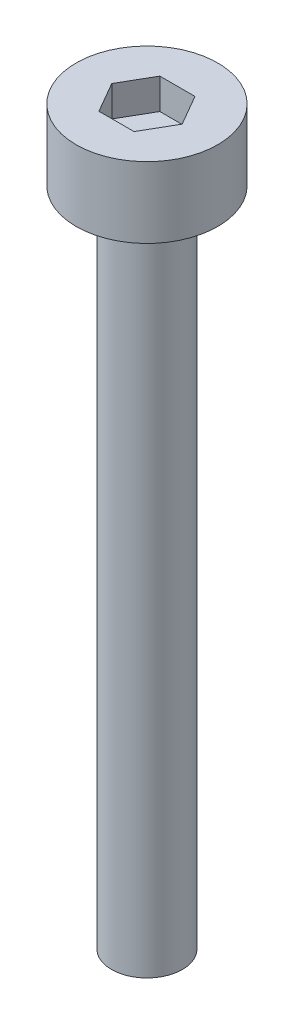
SolidWorks part; units mm, degrees
ref_plane "Front Plane" through (0, 0, 0) normal (0, 0, 1) x (1, 0, 0)
ref_plane "Top Plane" through (0, 0, 0) normal (0, 1, 0) x (1, 0, 0)
ref_plane "Right Plane" through (0, 0, 0) normal (1, 0, 0) x (0, 0, -1)
sketch "Sketch1" plane through (0, 0, 0) normal (0, 1, 0) x (1, 0, 0)
  circle A0 centre (0, 0) radius 1.5
  dimension "D1" = 3
extrude "ScrewShaft" add sketch "Sketch1" along normal blind 28
sketch "Sketch2" plane through (0, 28, 0) normal (0, 1, 0) x (1, 0, 0)
  circle A0 centre (0, 0) radius 3
  dimension "D1" = 6
extrude "Boss-Extrude2" add sketch "Sketch2" along normal blind 3
sketch "Sketch3" plane through (0, 31, 0) normal (0, 1, 0) x (1, 0, 0)
  line L0 (0, 0) -> (0, 1.29) construction
  line L1 (1.4896, 0) -> (0.7448, 1.29)
  line L2 (0.7448, 1.29) -> (-0.7448, 1.29)
  line L3 (-0.7448, 1.29) -> (-1.4896, 0)
  line L4 (-1.4896, 0) -> (-0.7448, -1.29)
  line L5 (-0.7448, -1.29) -> (0.7448, -1.29)
  line L6 (0.7448, -1.29) -> (1.4896, 0)
  circle A0 centre (0, 0) radius 1.29 construction
  dimension "D1" = 2.58
extrude "Cut-Extrude1" cut sketch "Sketch3" against normal blind 1.3
equation "\"X-ROD-SPACING\"=45"
equation "\"Y-ROD-SPACING\"=75"
equation "\"Z-ROD-SPACING\"=17.5"
equation "\"Y-BED-OFFSET\"=2"
equation "\"Y-BED-ROD-INSET\"=3.5"
equation "\"T-SLOT-NUT-FILLET-RADIUS\"=0.5"
equation "\"T-SLOT-SCREW-SHAFT-RADIUS\"=1.55"
equation "\"T-SLOT-SCREW-SHAFT-CUTOUT-LENGTH\"=11"
equation "\"T-SLOT-NUT-DEPTH\"=3.5"
equation "\"T-SLOT-NUT-WIDTH\"=2.85"
equation "\"T-SLOT-NUT-END-DISTANCE\"=8"
equation "\"ACRYLIC-THICKNESS\"=10"
equation "\"ACRYLIC-THICKNESS2\"=4.5"
equation "\"ACRYLIC-TAB-CUTOUT-SIZE\"=\"ACRYLIC-THICKNESS\"+\"ACRYLIC-TAB-TOLERANCE\"*2"
equation "\"ACRYLIC-TAB-WIDTH\"=\"ACRYLIC-THICKNESS\""
equation "\"ACRYLIC-M3-HOLE\"=2.9"
equation "\"SMOOTHROD-CAP-SCREW-DISTANCE\"=20"
equation "\"FRAME-WIDTH-INNER\"=370"
equation "\"NEMA17-HOLE-SPACING\"=31"
equation "\"NEMA17-CENTRAL-CUTOUT\"=22.5"
equation "\"Z-BRACKET-REACH\"=57"
equation "\"TOP-BRACKET-SPACING\"=40"
equation "\"SMOOTHROD-X-LENGTH\"=350"
equation "\"SMOOTHROD-Y-LENGTH\"=350"
equation "\"SMOOTHROD-Z-LENGTH\"=350"
equation "\"SMOOTHROD-TIGHTENING-HEADROOM\"=.25"
equation "\"LEADSCREW-Z-LENGTH\"=300"
equation "\"SCREW-LENGTH-FRAME\"=\"ACRYLIC-THICKNESS\" + 10"
equation "\"SCREW-HEAD-RADIUS\"=6"
equation "\"PRINTED-X-SMOOTHROD-DIAMETER\"=8.8"
equation "\"PRINTED-X-SMOOTHROD-CUTOUT\"=10"
equation "\"PRINTED-X-BASE-HEIGHT\"=10"
equation "\"PRINTED-LM8UU-CUTOUT-SIZE\"=15.5"
equation "\"PRINTED-LM8UU-CUTOUT-LENGTH\"=24.5"
equation "\"PRINTED-X-IDLER-HEIGHT\"=16"
equation "\"PSU-MOUNTING-WIDTH\"=95"
equation "\"PSU-MOUNTING-HEIGHT\"=177"
equation "\"D1@ScrewShaft\"=\"SCREW-LENGTH-EXTRUDER\""
equation "\"D1@Sketch2\"=\"SCREW-HEAD-RADIUS\""
equation "\"Y-BED-SCREW-SPACING\"=209"
equation "\"Y-BED-SCREW-CUTOUT-SLOT-HEIGHT\"=2"
equation "\"Z-ROD-INSET\"=13.5"
equation "\"SCREW-LENGTH-MOTOR\"=\"ACRYLIC-THICKNESS\" + 5"
equation "\"SCREW-LENGTH-EXTRUDER\"=28"
equation "\"Y-BELT-TO-ROD-DISTANCE\"=20"
equation "\"SPOOL-HOLDER-ROD-SPACING\"=150"
equation "\"ACRYLIC-X-CARRIAGE-WIDTH\"=55"
equation "\"ACRYLIC-X-CARRIAGE-HEIGHT\"=75"
equation "\"ACRYLIC-X-CARRIAGE-CENTER-TAB-SPACING\"=14"
